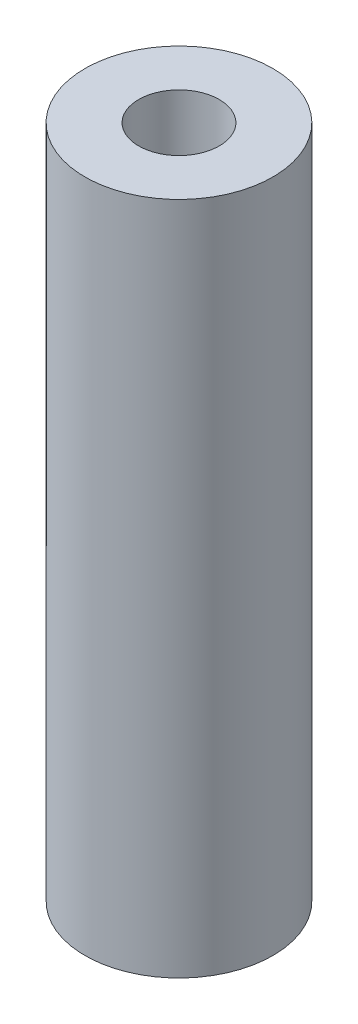
SolidWorks part; units mm, degrees
ref_plane "Front Plane" through (0, 0, 0) normal (0, 0, 1) x (1, 0, 0)
ref_plane "Top Plane" through (0, 0, 0) normal (0, 1, 0) x (1, 0, 0)
ref_plane "Right Plane" through (0, 0, 0) normal (1, 0, 0) x (0, 0, -1)
sketch "Sketch1" plane through (0, 0, 0) normal (0, 1, 0) x (1, 0, 0)
  circle A0 centre (0, 0) radius 4
  circle A1 centre (0, 0) radius 1.5875 construction
  circle A2 centre (0, 0) radius 1.7145
  dimension "D1" = 8
  dimension "D2" = 3.175
  dimension "D3" = 0.127
extrude "Boss-Extrude1" add sketch "Sketch1" along normal blind 28.7
